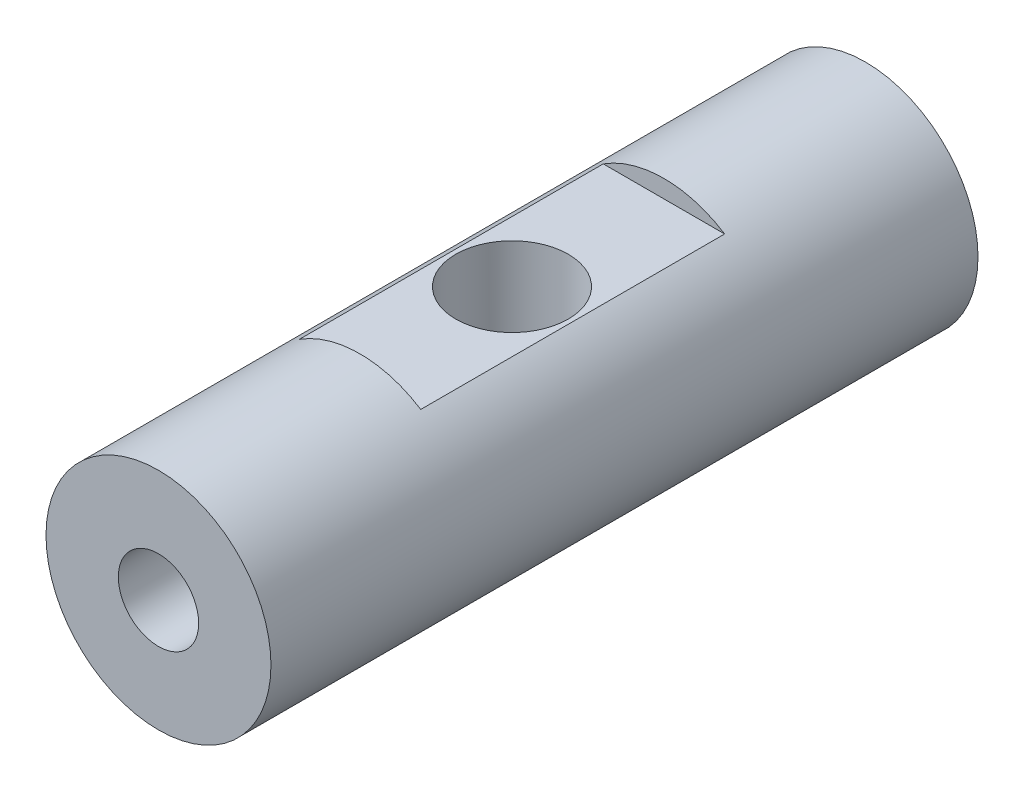
SolidWorks part; units mm, degrees
ref_plane "Front Plane" through (0, 0, 0) normal (0, 0, 1) x (1, 0, 0)
ref_plane "Top Plane" through (0, 0, 0) normal (0, 1, 0) x (1, 0, 0)
ref_plane "Right Plane" through (0, 0, 0) normal (1, 0, 0) x (0, 0, -1)
sketch "Sketch1" plane through (0, 0, 0) normal (0, 0, 1) x (1, 0, 0)
  circle A0 centre (0, 0) radius 7
  point P0 (0, 0)
  dimension "D1" = 14
extrude "Boss-Extrude1" add sketch "Sketch1" along normal blind 44
sketch "Sketch2" plane through (0, 0, 44) normal (0, 0, 1) x (1, 0, 0)
  circle A0 centre (0, 0) radius 2.5
  dimension "D1" = 5
extrude "Cut-Extrude1" cut sketch "Sketch2" against normal blind 10
sketch "Sketch3" plane through (0, 0, 0) normal (0, 0, -1) x (-1, 0, 0)
  circle A0 centre (0, 0) radius 2.5
  dimension "D1" = 5
extrude "Cut-Extrude2" cut sketch "Sketch3" against normal blind 10
sketch "Sketch4" plane through (0, 0, 0) normal (0, 1, 0) x (1, 0, 0)
  circle A0 centre (0, -22) radius 3.5
  dimension "D1" = 7
extrude "Cut-Extrude3" cut sketch "Sketch4" against normal mid plane 40
sketch "Sketch5" plane through (0, 0, 0) normal (1, 0, 0) x (0, 0, -1)
  line L3 (-12.5436, 8.107) -> (-31.4564, 8.107)
  line L4 (-12.5436, 8.107) -> (-12.5436, 5.893)
  line L5 (-12.5436, 5.893) -> (-31.4564, 5.893)
  line L6 (-31.4564, 8.107) -> (-31.4564, 5.893)
  line L10 (-12.5436, -8.107) -> (-12.5436, -5.893)
  line L11 (-12.5436, -8.107) -> (-31.4564, -8.107)
  line L12 (-31.4564, -8.107) -> (-31.4564, -5.893)
  line L13 (-12.5436, -5.893) -> (-31.4564, -5.893)
  point P8 (-22, 7)
extrude "Cut-Extrude5" cut sketch "Sketch5" against normal mid plane 70
